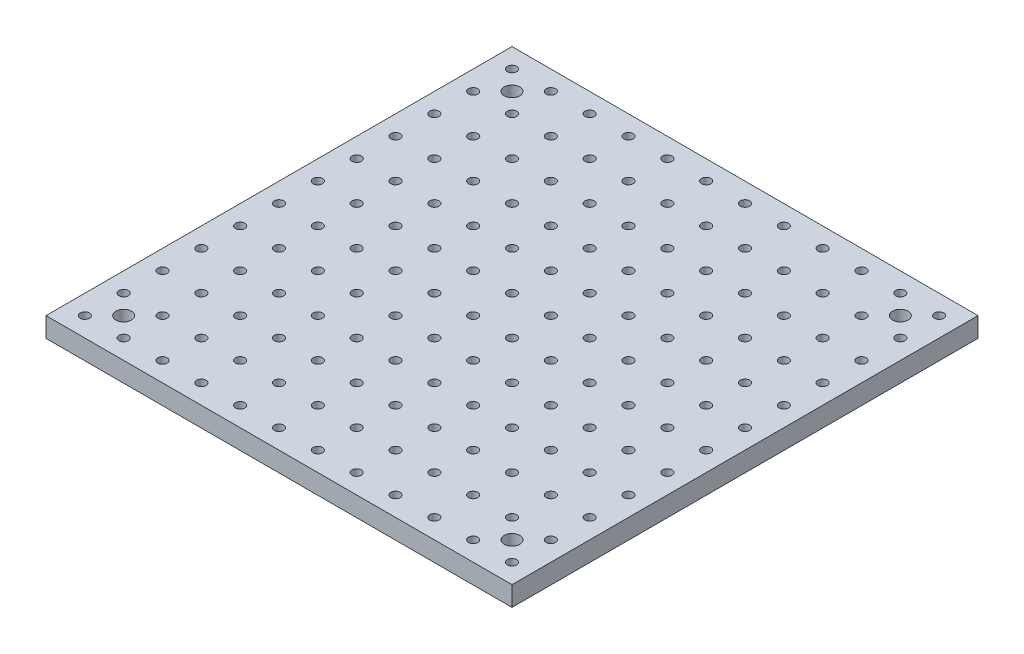
SolidWorks part; units mm, degrees
ref_plane "Front Plane" through (0, 0, 0) normal (0, 0, 1) x (1, 0, 0)
ref_plane "Top Plane" through (0, 0, 0) normal (0, 1, 0) x (1, 0, 0)
ref_plane "Right Plane" through (0, 0, 0) normal (1, 0, 0) x (0, 0, -1)
sketch "Sketch1" plane through (0, 0, 0) normal (0, 1, 0) x (1, 0, 0)
  line L1 (-150, -150) -> (150, -150)
  line L2 (-150, -150) -> (-150, 150)
  line L3 (-150, 150) -> (150, 150)
  line L4 (150, -150) -> (150, 150)
  line L5 (-150, -150) -> (150, 150) construction
  line L6 (-150, 150) -> (150, -150) construction
  point P0 (0, 0)
  dimension "D1" = 300
  dimension "D2" = 300
extrude "Boss-Extrude1" add sketch "Sketch1" along normal blind 12.7
sketch "Sketch2" plane through (0, 12.7, 0) normal (0, 1, 0) x (1, 0, 0)
  line L0 (-150, -150) -> (150, -150) construction
  line L1 (-150, 150) -> (-150, -150) construction
  circle A0 centre (-137.5, -137.5) radius 3
  circle A1 centre (-112.5, -137.5) radius 3
  circle A2 centre (-87.5, -137.5) radius 3
  circle A3 centre (-62.5, -137.5) radius 3
  circle A4 centre (-37.5, -137.5) radius 3
  circle A5 centre (-12.5, -137.5) radius 3
  circle A6 centre (12.5, -137.5) radius 3
  circle A7 centre (37.5, -137.5) radius 3
  circle A8 centre (62.5, -137.5) radius 3
  circle A9 centre (87.5, -137.5) radius 3
  circle A10 centre (112.5, -137.5) radius 3
  circle A11 centre (137.5, -137.5) radius 3
  circle A12 centre (-112.5, -112.5) radius 3
  circle A13 centre (-87.5, -112.5) radius 3
  circle A14 centre (-62.5, -112.5) radius 3
  circle A15 centre (-37.5, -112.5) radius 3
  circle A16 centre (-12.5, -112.5) radius 3
  circle A17 centre (12.5, -112.5) radius 3
  circle A18 centre (37.5, -112.5) radius 3
  circle A19 centre (62.5, -112.5) radius 3
  circle A20 centre (87.5, -112.5) radius 3
  circle A21 centre (112.5, -112.5) radius 3
  circle A22 centre (137.5, -112.5) radius 3
  circle A23 centre (-112.5, -87.5) radius 3
  circle A24 centre (-87.5, -87.5) radius 3
  circle A25 centre (-62.5, -87.5) radius 3
  circle A26 centre (-37.5, -87.5) radius 3
  circle A27 centre (-12.5, -87.5) radius 3
  circle A28 centre (12.5, -87.5) radius 3
  circle A29 centre (37.5, -87.5) radius 3
  circle A30 centre (62.5, -87.5) radius 3
  circle A31 centre (87.5, -87.5) radius 3
  circle A32 centre (112.5, -87.5) radius 3
  circle A33 centre (137.5, -87.5) radius 3
  circle A34 centre (-112.5, -62.5) radius 3
  circle A35 centre (-87.5, -62.5) radius 3
  circle A36 centre (-62.5, -62.5) radius 3
  circle A37 centre (-37.5, -62.5) radius 3
  circle A38 centre (-12.5, -62.5) radius 3
  circle A39 centre (12.5, -62.5) radius 3
  circle A40 centre (37.5, -62.5) radius 3
  circle A41 centre (62.5, -62.5) radius 3
  circle A42 centre (87.5, -62.5) radius 3
  circle A43 centre (112.5, -62.5) radius 3
  circle A44 centre (137.5, -62.5) radius 3
  circle A45 centre (-112.5, -37.5) radius 3
  circle A46 centre (-87.5, -37.5) radius 3
  circle A47 centre (-62.5, -37.5) radius 3
  circle A48 centre (-37.5, -37.5) radius 3
  circle A49 centre (-12.5, -37.5) radius 3
  circle A50 centre (12.5, -37.5) radius 3
  circle A51 centre (37.5, -37.5) radius 3
  circle A52 centre (62.5, -37.5) radius 3
  circle A53 centre (87.5, -37.5) radius 3
  circle A54 centre (112.5, -37.5) radius 3
  circle A55 centre (137.5, -37.5) radius 3
  circle A56 centre (-112.5, -12.5) radius 3
  circle A57 centre (-87.5, -12.5) radius 3
  circle A58 centre (-62.5, -12.5) radius 3
  circle A59 centre (-37.5, -12.5) radius 3
  circle A60 centre (-12.5, -12.5) radius 3
  circle A61 centre (12.5, -12.5) radius 3
  circle A62 centre (37.5, -12.5) radius 3
  circle A63 centre (62.5, -12.5) radius 3
  circle A64 centre (87.5, -12.5) radius 3
  circle A65 centre (112.5, -12.5) radius 3
  circle A66 centre (137.5, -12.5) radius 3
  circle A67 centre (-112.5, 12.5) radius 3
  circle A68 centre (-87.5, 12.5) radius 3
  circle A69 centre (-62.5, 12.5) radius 3
  circle A70 centre (-37.5, 12.5) radius 3
  circle A71 centre (-12.5, 12.5) radius 3
  circle A72 centre (12.5, 12.5) radius 3
  circle A73 centre (37.5, 12.5) radius 3
  circle A74 centre (62.5, 12.5) radius 3
  circle A75 centre (87.5, 12.5) radius 3
  circle A76 centre (112.5, 12.5) radius 3
  circle A77 centre (137.5, 12.5) radius 3
  circle A78 centre (-112.5, 37.5) radius 3
  circle A79 centre (-87.5, 37.5) radius 3
  circle A80 centre (-62.5, 37.5) radius 3
  circle A81 centre (-37.5, 37.5) radius 3
  circle A82 centre (-12.5, 37.5) radius 3
  circle A83 centre (12.5, 37.5) radius 3
  circle A84 centre (37.5, 37.5) radius 3
  circle A85 centre (62.5, 37.5) radius 3
  circle A86 centre (87.5, 37.5) radius 3
  circle A87 centre (112.5, 37.5) radius 3
  circle A88 centre (137.5, 37.5) radius 3
  circle A89 centre (-112.5, 62.5) radius 3
  circle A90 centre (-87.5, 62.5) radius 3
  circle A91 centre (-62.5, 62.5) radius 3
  circle A92 centre (-37.5, 62.5) radius 3
  circle A93 centre (-12.5, 62.5) radius 3
  circle A94 centre (12.5, 62.5) radius 3
  circle A95 centre (37.5, 62.5) radius 3
  circle A96 centre (62.5, 62.5) radius 3
  circle A97 centre (87.5, 62.5) radius 3
  circle A98 centre (112.5, 62.5) radius 3
  circle A99 centre (137.5, 62.5) radius 3
  circle A100 centre (-112.5, 87.5) radius 3
  circle A101 centre (-87.5, 87.5) radius 3
  circle A102 centre (-62.5, 87.5) radius 3
  circle A103 centre (-37.5, 87.5) radius 3
  circle A104 centre (-12.5, 87.5) radius 3
  circle A105 centre (12.5, 87.5) radius 3
  circle A106 centre (37.5, 87.5) radius 3
  circle A107 centre (62.5, 87.5) radius 3
  circle A108 centre (87.5, 87.5) radius 3
  circle A109 centre (112.5, 87.5) radius 3
  circle A110 centre (137.5, 87.5) radius 3
  circle A111 centre (-112.5, 112.5) radius 3
  circle A112 centre (-87.5, 112.5) radius 3
  circle A113 centre (-62.5, 112.5) radius 3
  circle A114 centre (-37.5, 112.5) radius 3
  circle A115 centre (-12.5, 112.5) radius 3
  circle A116 centre (12.5, 112.5) radius 3
  circle A117 centre (37.5, 112.5) radius 3
  circle A118 centre (62.5, 112.5) radius 3
  circle A119 centre (87.5, 112.5) radius 3
  circle A120 centre (112.5, 112.5) radius 3
  circle A121 centre (137.5, 112.5) radius 3
  circle A122 centre (-112.5, 137.5) radius 3
  circle A123 centre (-87.5, 137.5) radius 3
  circle A124 centre (-62.5, 137.5) radius 3
  circle A125 centre (-37.5, 137.5) radius 3
  circle A126 centre (-12.5, 137.5) radius 3
  circle A127 centre (12.5, 137.5) radius 3
  circle A128 centre (37.5, 137.5) radius 3
  circle A129 centre (62.5, 137.5) radius 3
  circle A130 centre (87.5, 137.5) radius 3
  circle A131 centre (112.5, 137.5) radius 3
  circle A132 centre (137.5, 137.5) radius 3
  circle A133 centre (-137.5, -112.5) radius 3
  circle A134 centre (-137.5, -87.5) radius 3
  circle A135 centre (-137.5, -62.5) radius 3
  circle A136 centre (-137.5, -37.5) radius 3
  circle A137 centre (-137.5, -12.5) radius 3
  circle A138 centre (-137.5, 12.5) radius 3
  circle A139 centre (-137.5, 37.5) radius 3
  circle A140 centre (-137.5, 62.5) radius 3
  circle A141 centre (-137.5, 87.5) radius 3
  circle A142 centre (-137.5, 112.5) radius 3
  circle A143 centre (-137.5, 137.5) radius 3
  circle A144 centre (-125, -125) radius 5
  circle A145 centre (125, -125) radius 5
  circle A146 centre (125, 125) radius 5
  circle A147 centre (-125, 125) radius 5
  dimension "D1" = 6
  dimension "D6" = 10
  dimension "D2" = 12.5
  dimension "D3" = 12.5
  dimension "D7" = 25
  dimension "D8" = 25
  dimension "D4" = 12
  dimension "D5" = 12
  dimension "D9" = 2
  dimension "D10" = 2
extrude "Cut-Extrude1" cut sketch "Sketch2" against normal up to surface (12.7 mm away) up to face at (0, 0, 0)
